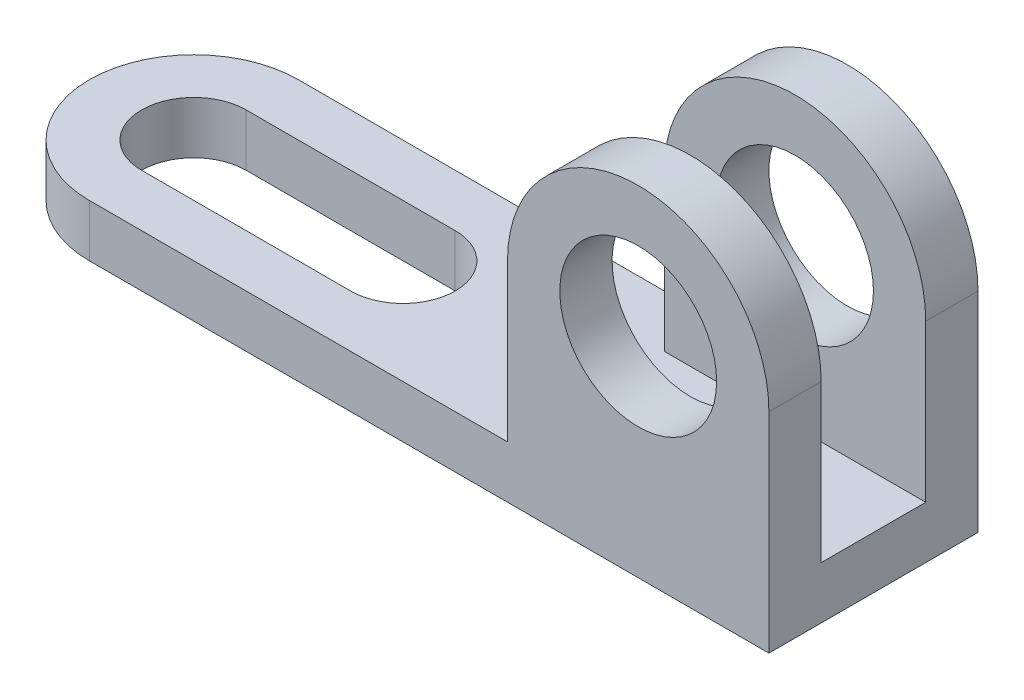
SolidWorks part; units mm, degrees
ref_plane "Ön Düzlem" through (0, 0, 0) normal (0, 0, 1) x (1, 0, 0)
ref_plane "Üst Düzlem" through (0, 0, 0) normal (0, 1, 0) x (1, 0, 0)
ref_plane "Sağ Düzlem" through (0, 0, 0) normal (1, 0, 0) x (0, 0, -1)
sketch "Çizim1" plane through (0, 0, 0) normal (0, 1, 0) x (1, 0, 0)
  line L0 (-40, 0) -> (52.9101, 0) construction
  line L1 (-40, 20) -> (52.9101, 20)
  line L2 (-40, -20) -> (52.9101, -20)
  line L3 (-40, 0) -> (0, 0) construction
  line L4 (18.6243, 20) -> (90, 20)
  line L6 (26.7196, -20) -> (90, -20)
  line L7 (90, 20) -> (90, -20)
  line L8 (-40, 10) -> (0, 10)
  line L9 (-40, -10) -> (0, -10)
  arc A0 (-40, 20) -> (-40, -20) centre (-40, 0) ccw
  arc A2 (-40, 10) -> (-40, -10) centre (-40, 0) ccw
  arc A3 (0, -10) -> (0, 10) centre (0, 0) ccw
  point P3 (1.164, 0)
  point P12 (-20, 0)
  point P18 (-99.7316, 0)
  point P19 (52.9101, 0)
  dimension "D1" = 20
  dimension "D2" = 10
  dimension "D3" = 40
  dimension "D4" = 130
  dimension "D5" = 40
extrude "Yükseklik-Ekstrüzyon1" add sketch "Çizim1" along normal blind 10 contours L1 A0 L2 L6 L7 L4 A3 L9 A2 L8
sketch "Çizim2" plane through (0, 0, 20) normal (0, 0, 1) x (1, 0, 0)
  line L1 (90, 10) -> (40, 10)
  line L2 (90, 10) -> (90, 40)
  line L4 (40, 10) -> (40, 40)
  circle A0 centre (65, 40) radius 15
  arc A1 (90, 40) -> (40, 40) centre (65, 40) ccw
  point P9 (0, 0)
  point P10 (0, 0)
  dimension "D2" = 30
  dimension "D3" = 50
  dimension "D1" = 40
  dimension "D4" = 50
extrude "Yükseklik-Ekstrüzyon6" add sketch "Çizim2" against normal blind 40 contours L2 L1 L4 A1
sketch "Çizim6" plane through (0, 0, 20) normal (0, 0, 1) x (1, 0, 0)
  circle A0 centre (65, 40) radius 15
  point P2 (0, 0)
  dimension "D1" = 30
  dimension "D2" = 40
  dimension "D3" = 25
extrude "Kes-Ekstrüzyon1" cut sketch "Çizim6" against normal blind 40 contours A0
sketch "Çizim7" plane through (90, 0, 0) normal (1, 0, 0) x (0, 0, -1)
  line L0 (20, 65) -> (-20, 65) construction
  line L1 (-10, 65) -> (10, 65)
  line L2 (-10, 65) -> (-10, 10)
  line L3 (-10, 10) -> (10, 10)
  line L4 (10, 65) -> (10, 10)
  dimension "D1" = 20
  dimension "D2" = 10
  dimension "D3" = 10
extrude "Kes-Ekstrüzyon2" cut sketch "Çizim7" against normal blind 50
